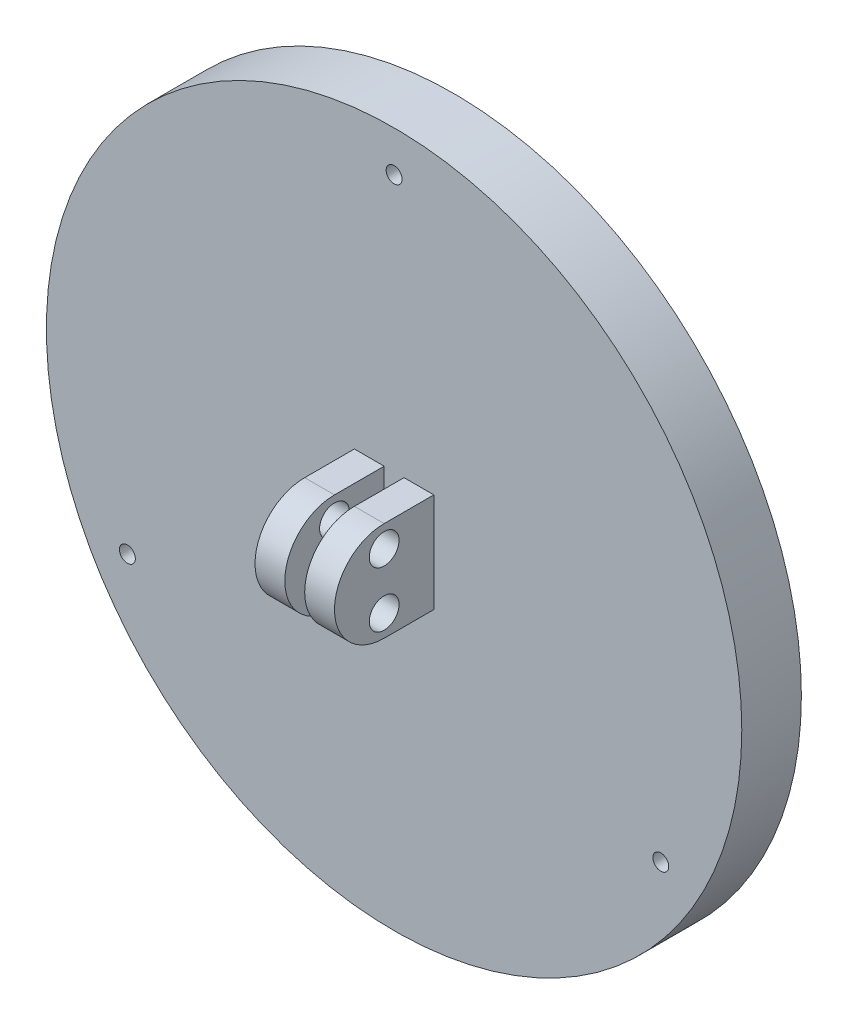
SolidWorks part; units mm, degrees
ref_plane "Front Plane" through (0, 0, 0) normal (0, 0, 1) x (1, 0, 0)
ref_plane "Top Plane" through (0, 0, 0) normal (0, 1, 0) x (1, 0, 0)
ref_plane "Right Plane" through (0, 0, 0) normal (1, 0, 0) x (0, 0, -1)
sketch "Sketch2" plane through (0, 0, 0) normal (0, 0, 1) x (1, 0, 0)
  circle A0 centre (0, 0) radius 35
  point P11 (0, 0)
  dimension "D1" = 70
extrude "Boss-Extrude1" add sketch "Sketch2" along normal blind 6 contours A0
sketch "Sketch3" plane through (0, 0, 6) normal (0, 0, 1) x (1, 0, 0)
  circle A0 centre (0, 30.9143) radius 0.8
  circle A1 centre (26.8468, -15.5857) radius 0.8
  circle A2 centre (-26.8468, -15.5857) radius 0.8
  point P8 (0, -0.0857)
  dimension "D1" = 1.6
  dimension "D3" = 31
  dimension "D2" = 3
extrude "Cut-Extrude1" cut sketch "Sketch3" against normal blind 6
sketch "Sketch4" plane through (0, 0, 6) normal (0, 0, 1) x (1, 0, 0)
  circle A0 centre (0, 0) radius 0.6
  dimension "D1" = 1.2
extrude "Cut-Extrude2" cut sketch "Sketch4" against normal blind 6
sketch "Sketch5" plane through (0, 0, 6) normal (0, 0, 1) x (1, 0, 0)
  line L1 (1, 5) -> (4, 5)
  line L2 (1, 5) -> (1, -5)
  line L3 (1, -5) -> (4, -5)
  line L4 (4, 5) -> (4, -5)
  line L5 (-1, 5) -> (-4, 5)
  line L6 (-1, 5) -> (-1, -5)
  line L7 (-1, -5) -> (-4, -5)
  line L8 (-4, 5) -> (-4, -5)
  dimension "D1" = 10
  dimension "D2" = 3
  dimension "D3" = 4
  dimension "D4" = 5
  dimension "D5" = 4
  dimension "D6" = 5
extrude "Boss-Extrude2" add sketch "Sketch5" along normal blind 10
sketch "Sketch6" plane through (4, 0, 0) normal (1, 0, 0) x (0, 0, -1)
  line L1 (-16, 5) -> (-6, 5) construction
  line L2 (-11, 5) -> (-16, 5)
  line L3 (-16, 5) -> (-16, -5)
  line L5 (-16, -5) -> (-11, -5)
  line L6 (-16, 5) -> (-11, 5)
  arc A2 (-11, -5) -> (-11, 5) centre (-11, 0) cw
  line M5 (-6, 5) -> (-16, 5)
  line M6 (-16, 5) -> (-16, -5)
  line M7 (-16, -5) -> (-6, -5)
extrude "Cut-Extrude3" cut sketch "Sketch6" against normal through all contours A2 M6 M5 | A2 L3 M7
sketch "Sketch7" plane through (4, 0, 0) normal (1, 0, 0) x (0, 0, -1)
  line L1 (-11, 5) -> (-6, 5) construction
  line L2 (-11, -5) -> (-6, -5) construction
  circle A2 centre (-11, 2.8) radius 1.5
  circle A3 centre (-11, -2.8) radius 1.5
  dimension "D1" = 2.2
  dimension "D2" = 2.2
  dimension "D4" = 3
extrude "Cut-Extrude4" cut sketch "Sketch7" against normal through all
